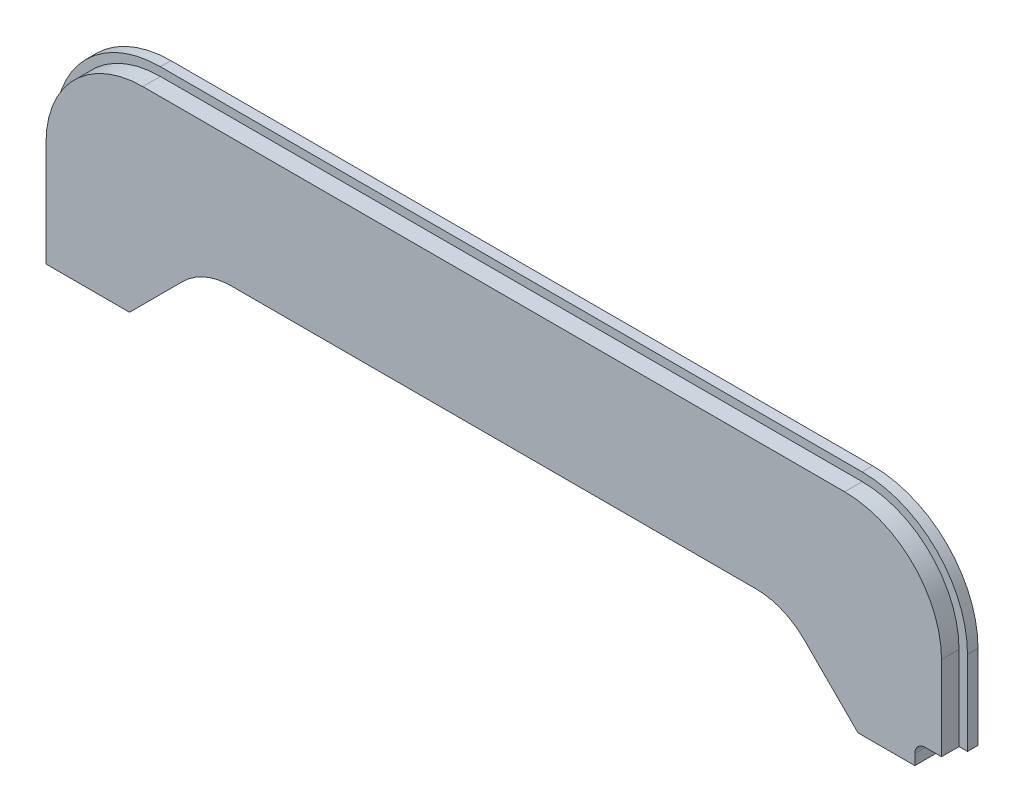
SolidWorks part; units mm, degrees
ref_plane "Front" through (0, 0, 0) normal (0, 0, 1) x (1, 0, 0)
ref_plane "Top" through (0, 0, 0) normal (0, 1, 0) x (1, 0, 0)
ref_plane "Right" through (0, 0, 0) normal (1, 0, 0) x (0, 0, -1)
sketch "Sketch1" plane through (0, 0, 0) normal (0, 0, 1) x (1, 0, 0)
  line L1 (-12.7, 7.62) -> (12.7, 7.62)
  line L2 (-16.51, 3.81) -> (-16.51, 0)
  line L3 (-16.51, 0) -> (16.51, 0)
  line L4 (16.51, 3.81) -> (16.51, 0)
  arc A0 (12.7, 7.62) -> (16.51, 3.81) centre (12.7, 3.81) cw
  arc A1 (-12.7, 7.62) -> (-16.51, 3.81) centre (-12.7, 3.81) ccw
  dimension "D3" = 3.81
  dimension "D1" = 33.02
  dimension "D2" = 7.62
extrude "Boss-Extrude1" add sketch "Sketch1" along normal blind 1.016
sketch "Sketch2" plane through (0, 0, 1.016) normal (0, 0, 1) x (1, 0, 0)
  line L4 (-16.51, 0) -> (16.51, 0) construction
  line L5 (16.2052, 0) -> (16.51, 0)
  line L8 (16.2052, 0.3048) -> (16.2052, 3.81)
  line L9 (12.7, 7.3152) -> (-12.7, 7.3152)
  line L10 (-16.2052, 3.81) -> (-16.2052, 0.3048)
  line L11 (-16.2052, 0.3048) -> (16.2052, 0.3048)
  line L12 (16.2052, 0) -> (16.2052, 3.81)
  line L13 (12.7, 7.3152) -> (-12.7, 7.3152)
  line L14 (-16.2052, 3.81) -> (-16.2052, 0)
  line L16 (16.51, 0) -> (16.51, 3.81)
  line L17 (12.7, 7.62) -> (-12.7, 7.62)
  line L18 (-16.51, 3.81) -> (-16.51, 0)
  line L19 (-16.51, 0) -> (16.51, 0)
  line L20 (16.51, 0) -> (16.51, 3.81)
  line L21 (12.7, 7.62) -> (-12.7, 7.62)
  line L22 (-16.51, 3.81) -> (-16.51, 0)
  line L23 (-16.51, 0) -> (-16.2052, 0)
  arc A4 (16.2052, 3.81) -> (12.7, 7.3152) centre (12.7, 3.81) ccw
  arc A5 (-12.7, 7.3152) -> (-16.2052, 3.81) centre (-12.7, 3.81) ccw
  arc A6 (16.2052, 3.81) -> (12.7, 7.3152) centre (12.7, 3.81) ccw
  arc A7 (-12.7, 7.3152) -> (-16.2052, 3.81) centre (-12.7, 3.81) ccw
  arc A8 (16.51, 3.81) -> (12.7, 7.62) centre (12.7, 3.81) ccw
  arc A9 (-12.7, 7.62) -> (-16.51, 3.81) centre (-12.7, 3.81) ccw
  arc A10 (16.51, 3.81) -> (12.7, 7.62) centre (12.7, 3.81) ccw
  arc A11 (-12.7, 7.62) -> (-16.51, 3.81) centre (-12.7, 3.81) ccw
  dimension "D1" = 0.3048
  dimension "D2" = 0
extrude "Cut-Extrude1" cut sketch "Sketch2" against normal blind 0.635
sketch "Sketch3" plane through (0, 0, 1.016) normal (0, 0, 1) x (1, 0, 0)
  line L0 (-13.1826, 0) -> (-11.2447, 1.9379)
  line L1 (-16.2052, 0) -> (16.2052, 0) construction
  line L4 (-16.51, 3.81) -> (-16.51, 0) construction
  line L5 (0, 0) -> (0, 6.062) construction
  line L7 (13.1826, 0) -> (11.2447, 1.9379)
  line L8 (-13.1826, 0) -> (13.1826, 0)
  line L9 (-9.4845, 2.667) -> (9.4845, 2.667)
  arc A0 (-9.4845, 2.667) -> (-11.2447, 1.9379) centre (-9.4845, 0.1778) ccw
  arc A3 (9.4845, 2.667) -> (11.2447, 1.9379) centre (9.4845, 0.1778) cw
  point P22 (0, 0.381)
  dimension "D4" = 4.9784
  dimension "D8" = 2.667
  dimension "D2" = 45
  dimension "D7" = 3.3274
extrude "Cut-Extrude2" cut sketch "Sketch3" against normal through all
sketch "Sketch4" plane through (0, 0, 1.016) normal (0, 0, 1) x (1, 0, 0)
  line L1 (16.51, 0) -> (15.24, 0)
  line L2 (16.51, 0) -> (16.51, 0.762)
  line L3 (16.51, 0.762) -> (15.621, 0.762)
  line L4 (15.24, 0) -> (15.24, 0.381)
  arc A0 (15.621, 0.762) -> (15.24, 0.381) centre (15.621, 0.381) ccw
  dimension "D1" = 0.381
  dimension "D2" = 0.889
  dimension "D3" = 0.762
extrude "Cut-Extrude3" cut sketch "Sketch4" against normal through all
